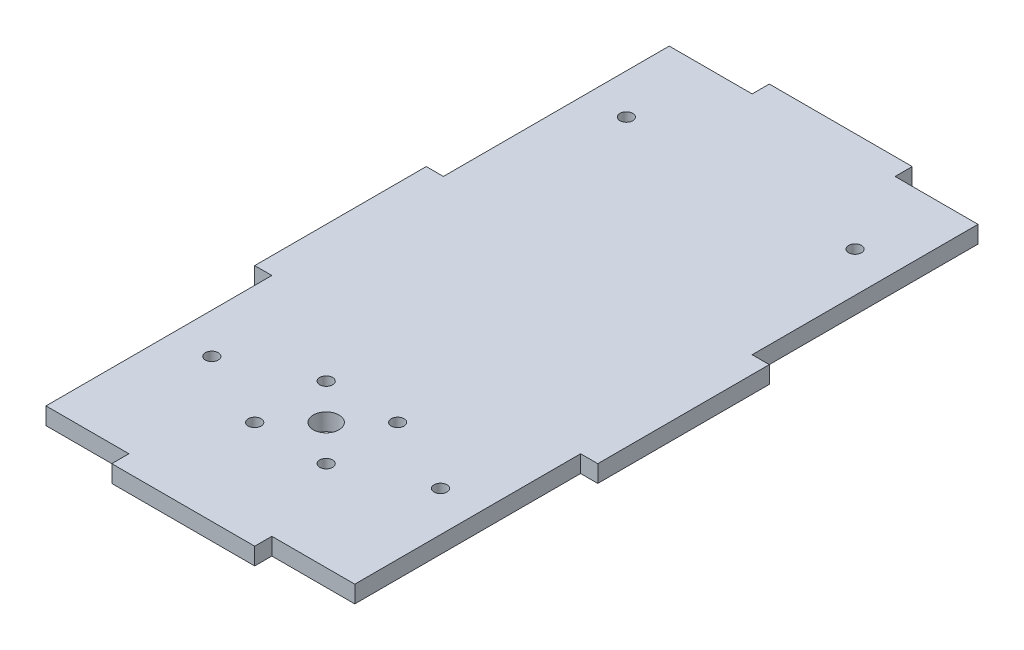
SolidWorks part; units mm, degrees
material "6061-T6 (SS)"
ref_plane "Alzado" through (0, 0, 0) normal (0, 0, 1) x (1, 0, 0)
ref_plane "Planta" through (0, 0, 0) normal (0, 1, 0) x (1, 0, 0)
ref_plane "Vista lateral" through (0, 0, 0) normal (1, 0, 0) x (0, 0, -1)
sketch "Croquis1" plane through (0, 0, 0) normal (0, 1, 0) x (1, 0, 0)
  line L0 (0, 0) -> (0, -115) construction
  line L1 (-54, -109) -> (-25, -109)
  line L2 (-54, -109) -> (-54, -30)
  line L3 (-54, 109) -> (-25, 109)
  line L4 (54, -109) -> (54, -30)
  line L5 (-54, -109) -> (54, 109) construction
  line L6 (-54, 109) -> (54, -109) construction
  line L7 (54, 30) -> (60, 30)
  line L9 (54, -30) -> (60, -30)
  line L10 (60, 30) -> (60, -30)
  line L11 (54, 30) -> (54, 109)
  line L12 (-54, -30) -> (-60, -30)
  line L13 (-54, 30) -> (-60, 30)
  line L14 (-60, 30) -> (-60, -30)
  line L15 (-54, 30) -> (-54, 109)
  line L16 (0, 0) -> (60, 0) construction
  line L18 (-25, 109) -> (-25, 115)
  line L19 (-25, 115) -> (25, 115)
  line L20 (25, 109) -> (25, 115)
  line L21 (25, -109) -> (25, -115)
  line L22 (-25, -115) -> (25, -115)
  line L23 (-25, -109) -> (-25, -115)
  line L24 (25, 109) -> (54, 109)
  line L25 (25, -109) -> (54, -109)
  point P0 (0, 0)
  point P12 (60, 0)
  point P21 (0, 115)
  dimension "D1" = 230
  dimension "D2" = 120
  dimension "D3" = 60
  dimension "D4" = 6
  dimension "D5" = 50
extrude "Saliente-Extruir1" add sketch "Croquis1" along normal mid plane 6
sketch "Croquis2" plane through (0, 0, 0) normal (0, 1, 0) x (1, 0, 0)
  circle A0 centre (0, -65) radius 4.5
  circle A1 centre (0, -65) radius 4.5 construction
extrude "Cortar-Extruir1" cut sketch "Croquis2" against normal through all both and the other way through all
hole_wizard "Taladro de margen para M42" positions "Croquis3" profile "Croquis4" hole size "M4" standard "Ansi Metric" end condition up to next
sketch "Croquis3" plane through (0, 3, 0) normal (0, 1, 0) x (1, 0, 0)
  point P0 (12.5, -77.5)
  point P3 (-12.5, -77.5)
  point P6 (12.5, -52.5)
  point P9 (-12.5, -52.5)
sketch "Croquis4" plane through (12.5, 3, 77.5) normal (1, 0, 0) x (0, 0, 1)
  line L0 (0, 0) -> (0, 6)
  line L1 (0, 6) -> (2.25, 6)
  line L2 (2.25, 6) -> (2.25, 0)
  line L5 (2.25, 0) -> (0, 0)
  line L11 (0, -6.35) -> (0, 107.95) construction
  dimension "Diámetro de taladro hasta el siguiente" = 4.5
  dimension "Profundidad de taladro hasta el siguiente" = 6
hole_wizard "Taladro de margen para M41" positions "Croquis5" profile "Croquis6" hole size "M4" standard "Ansi Metric" end condition up to next
sketch "Croquis5" plane through (0, -3, 0) normal (0, -1, 0) x (-1, 0, 0)
  point P0 (40, 80)
  point P3 (-40, 80)
  point P6 (40, -65)
  point P9 (-40, -65)
sketch "Croquis6" plane through (-40, -3, -80) normal (1, 0, 0) x (0, 0, -1)
  line L0 (0, 0) -> (0, 6)
  line L1 (0, 6) -> (2.25, 6)
  line L2 (2.25, 6) -> (2.25, 0)
  line L5 (2.25, 0) -> (0, 0)
  line L11 (0, -6.35) -> (0, 107.95) construction
  dimension "Diámetro de taladro hasta el siguiente" = 4.5
  dimension "Profundidad de taladro hasta el siguiente" = 6
